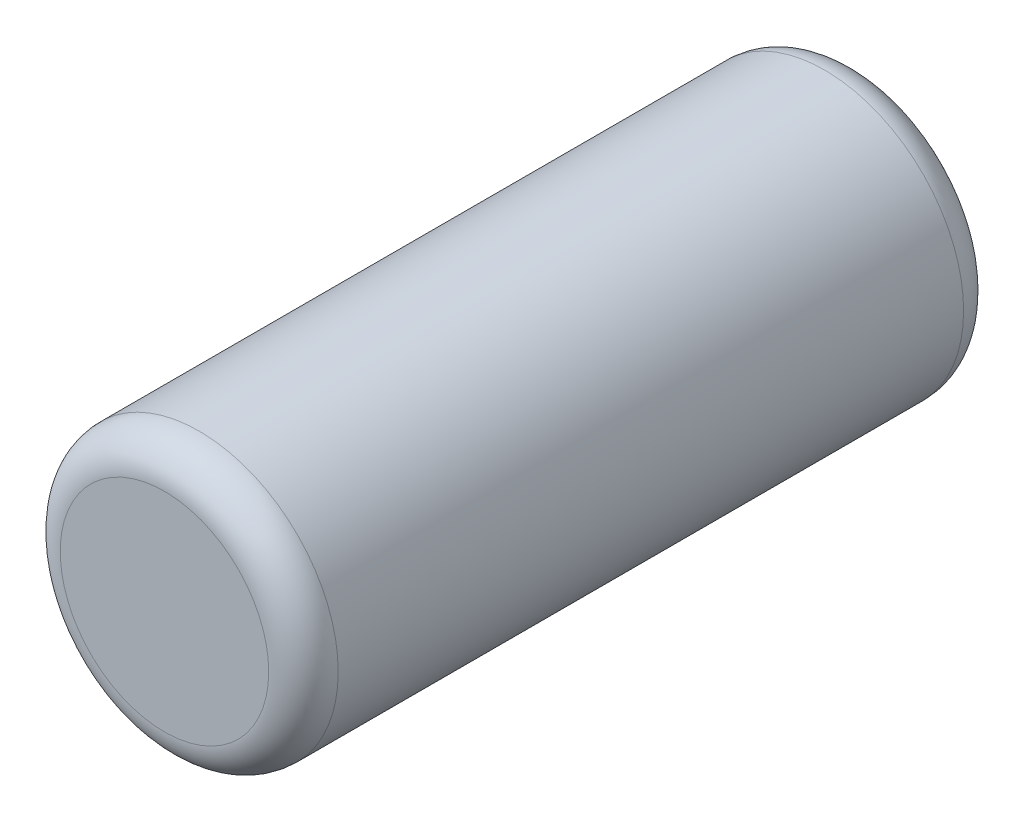
SolidWorks part; units mm, degrees
ref_plane "Plan1" through (0, 0, 0) normal (0, 0, 1) x (1, 0, 0)
ref_plane "Plan2" through (0, 0, 0) normal (0, 1, 0) x (1, 0, 0)
ref_plane "Plan3" through (0, 0, 0) normal (1, 0, 0) x (0, 0, -1)
sketch "Esquisse1" plane through (0, 0, 0) normal (0, 0, 1) x (1, 0, 0)
  circle A0 centre (0, 0) radius 4
  dimension "D1" = 8
extrude "Base-Extrusion" add sketch "Esquisse1" along normal blind 20
fillet "Congé1" radius 1 2 edges at (4, 0, 0) (4, 0, 20)
